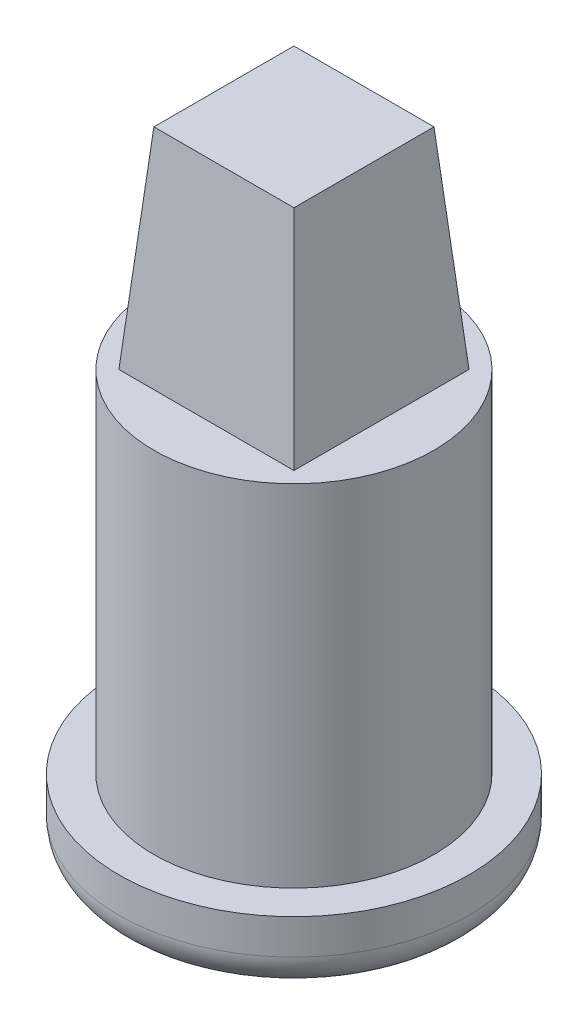
SolidWorks part; units mm, degrees
ref_plane "Front Plane" through (0, 0, 0) normal (0, 0, 1) x (1, 0, 0)
ref_plane "Top Plane" through (0, 0, 0) normal (0, 1, 0) x (1, 0, 0)
ref_plane "Right Plane" through (0, 0, 0) normal (1, 0, 0) x (0, 0, -1)
sketch "Sketch1" plane through (0, 0, 0) normal (0, 0, 1) x (1, 0, 0)
  line L0 (0, 0) -> (0, 24)
  line L1 (0, 24) -> (8, 24)
  line L2 (8, 24) -> (8, 4)
  line L3 (8, 4) -> (10, 4)
  line L4 (10, 4) -> (10, 2)
  line L5 (8, 0) -> (0, 0)
  arc A0 (10, 2) -> (8, 0) centre (8, 2) cw
  dimension "D1" = 2
revolve "Revolve1" add sketch "Sketch1" angle 360 about L0
sketch "Sketch2" plane through (0, 24, 0) normal (0, 1, 0) x (1, 0, 0)
  line L1 (-5, -5) -> (5, -5)
  line L2 (-5, -5) -> (-5, 5)
  line L3 (-5, 5) -> (5, 5)
  line L4 (5, -5) -> (5, 5)
  line L5 (-5, -5) -> (5, 5) construction
  line L6 (-5, 5) -> (5, -5) construction
  point P0 (0, 0)
ref_plane "Plane1" through (0, 36, 0) normal (0, 1, 0) x (1, 0, 0)
sketch "Sketch3" plane through (0, 36, 0) normal (0, 1, 0) x (1, 0, 0)
  line L0 (-5, -5) -> (5, 5) construction
  line L1 (-4, -4) -> (4, -4)
  line L2 (-4, -4) -> (-4, 4)
  line L3 (-4, 4) -> (4, 4)
  line L4 (4, -4) -> (4, 4)
  line L5 (-4, -4) -> (4, 4) construction
  line L6 (-4, 4) -> (4, -4) construction
  point P0 (0, 0)
loft "Loft1" add profiles "Sketch3", "Sketch2"
